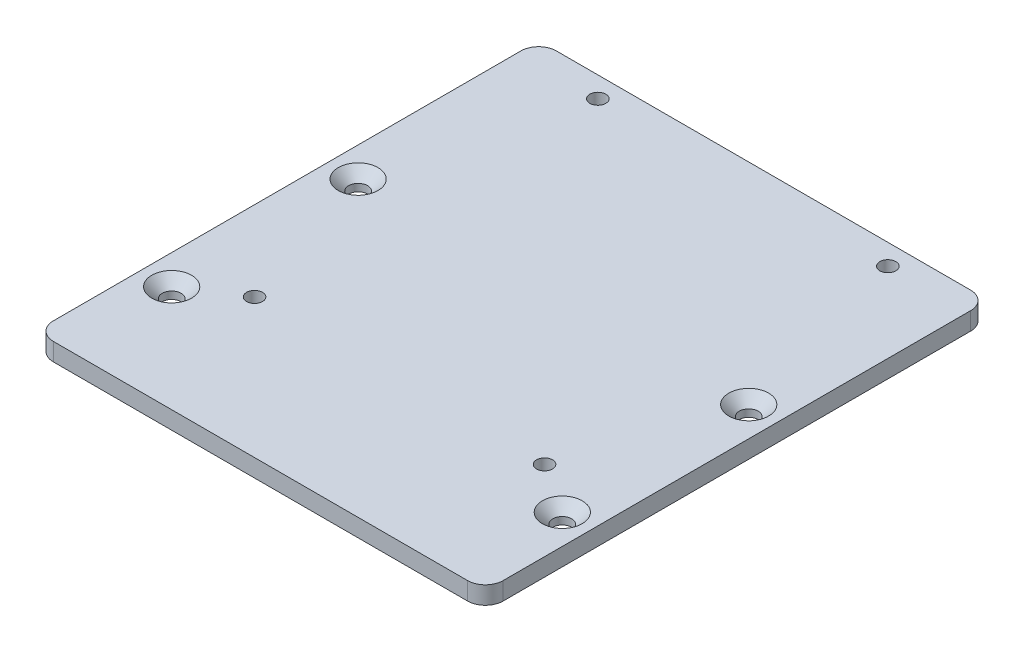
SolidWorks part; units mm, degrees
material "6061-T6 (SS)"
ref_plane "Front Plane" through (0, 0, 0) normal (0, 0, 1) x (1, 0, 0)
ref_plane "Top Plane" through (0, 0, 0) normal (0, 1, 0) x (1, 0, 0)
ref_plane "Right Plane" through (0, 0, 0) normal (1, 0, 0) x (0, 0, -1)
sketch "Sketch1" plane through (0, 0, 0) normal (0, 1, 0) x (1, 0, 0)
  line L0 (-33, 7) -> (-33, -24.5) construction
  line L1 (33, -24.5) -> (33, 7) construction
  line L2 (-33, 0) -> (33, 0) construction
  line L4 (38, -42.5) -> (-38, -42.5)
  line L5 (38, -42.5) -> (38, 42.5)
  line L6 (38, 42.5) -> (-38, 42.5)
  line L7 (-38, -42.5) -> (-38, 42.5)
  line L8 (38, -42.5) -> (-38, 42.5) construction
  line L9 (38, 42.5) -> (-38, -42.5) construction
  line L10 (24.5, -19) -> (-24.5, -19) construction
  line L11 (24.5, -19) -> (24.5, 39) construction
  line L12 (24.5, 39) -> (-24.5, 39) construction
  line L13 (-24.5, -19) -> (-24.5, 39) construction
  line L14 (24.5, -19) -> (-24.5, 39) construction
  line L15 (24.5, 39) -> (-24.5, -19) construction
  point P4 (0, 0)
  point P7 (0, 10)
  point P12 (0, 0)
  dimension "D1" = 31.5
  dimension "D2" = 7
  dimension "D3" = 85
  dimension "D4" = 76
  dimension "D5" = 49
  dimension "D6" = 58
  dimension "D7" = 3.5
  dimension "D8" = 5
extrude "Boss-Extrude1" add sketch "Sketch1" along normal blind 3
hole_wizard "M2.5 Clearance Hole1" positions "Sketch2" profile "Sketch3" hole size "M2.5" standard "ANSI Metric" end condition through all
sketch "Sketch2" plane through (0, 3, 0) normal (0, 1, 0) x (1, 0, 0)
  point P0 (-24.5, 39)
  point P3 (-24.5, -19)
  point P6 (24.5, -19)
  point P9 (24.5, 39)
sketch "Sketch3" plane through (-24.5, 3, -39) normal (1, 0, 0) x (0, 0, 1)
  line L0 (0, 0) -> (0, 3)
  line L1 (0, 3) -> (1.35, 3)
  line L2 (1.35, 3) -> (1.35, 0)
  line L5 (1.35, 0) -> (0, 0)
  line L11 (0, -6.35) -> (0, 107.95) construction
  dimension "Thru Hole Dia." = 2.7
  dimension "Thru Hole Depth" = 3
hole_wizard "CSK for M3 SFHCS1" positions "Sketch4" profile "Sketch5" countersink size "M3" standard "ANSI Metric" end condition through all
sketch "Sketch4" plane through (0, 3, 0) normal (0, 1, 0) x (1, 0, 0)
  point P0 (-33, -24.5)
  point P3 (-33, 7)
  point P6 (33, 7)
  point P9 (33, -24.5)
sketch "Sketch5" plane through (-33, 3, 24.5) normal (1, 0, 0) x (0, 0, 1)
  line L0 (0, 0) -> (0, 3)
  line L1 (0, 3) -> (1.6, 3)
  line L2 (1.6, 3) -> (1.6, 1.76)
  line L3 (1.6, 1.76) -> (3.36, 0)
  line L5 (3.36, 0) -> (0, 0)
  line L6 (-1.6, 1.76) -> (-3.36, 0) construction
  line L11 (0, -6.35) -> (0, 107.95) construction
  dimension "Thru Hole Dia." = 3.2
  dimension "Thru Hole Depth" = 3
  dimension "Near C'Sink Dia." = 6.72
  dimension "Near C'Sink Angle" = 90
fillet "Fillet1" radius 3 4 edges at (-38, 1.5, -42.5) (38, 1.5, -42.5) (38, 1.5, 42.5) (-38, 1.5, 42.5)
